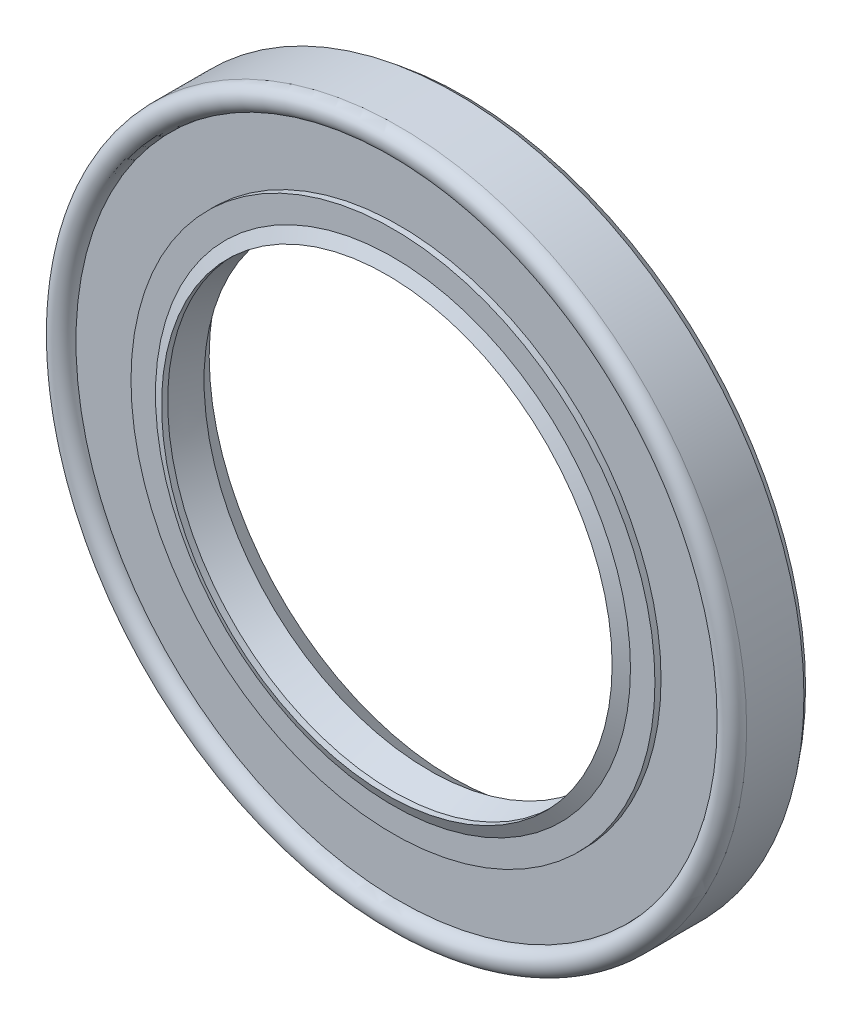
SolidWorks part; units mm, degrees
ref_plane "Front" through (0, 0, 0) normal (0, 0, 1) x (1, 0, 0)
ref_plane "Top" through (0, 0, 0) normal (0, 1, 0) x (1, 0, 0)
ref_plane "Right" through (0, 0, 0) normal (1, 0, 0) x (0, 0, -1)
sketch "Sketch1" plane through (0, 0, 0) normal (1, 0, 0) x (0, 0, -1)
  line L0 (-3.175, 17.5) -> (-2.7, 17.5)
  line L1 (-2.7, 17.5) -> (-2.225, 18.45)
  line L2 (-2.225, 18.45) -> (0.125, 17.5)
  line L3 (0.125, 17.5) -> (1.95, 18.925)
  line L4 (1.95, 18.925) -> (1.95, 19.4)
  line L5 (1.95, 19.4) -> (1.075, 19.4)
  line L6 (-0.825, 19.4) -> (-1.275, 19.4)
  line L7 (-1.275, 19.4) -> (-1.275, 26.05)
  line L8 (-1.275, 26.05) -> (1.625, 26.05)
  line L9 (1.625, 26.05) -> (1.625, 26.2875)
  line L10 (1.625, 26.2875) -> (2.225, 26.2875)
  line L11 (2.225, 26.2875) -> (2.225, 26.05)
  line L12 (2.225, 26.05) -> (2.825, 26.05)
  line L13 (2.825, 26.05) -> (2.825, 26.525)
  line L14 (2.825, 26.525) -> (2.225, 27)
  line L15 (2.225, 27) -> (-2.225, 27)
  line L16 (-2.225, 25.1) -> (-2.225, 20.35)
  line L17 (-2.225, 20.35) -> (-2.7, 20.35)
  line L18 (-2.7, 20.35) -> (-2.7, 18.45)
  line L19 (-2.7, 18.45) -> (-3.175, 17.5)
  line L20 (3.175, 0) -> (-3.175, 0) construction
  line L21 (-2.7, 17.5) -> (0.125, 17.5) construction
  line L22 (0, 27) -> (0, 26.05) construction
  line L23 (0, 26.05) -> (0, 25.1) construction
  line L24 (0, 25.1) -> (0, 24.15) construction
  line L25 (0, 24.15) -> (0, 23.2) construction
  line L26 (0, 23.2) -> (0, 22.25) construction
  line L27 (0, 22.25) -> (0, 21.3) construction
  line L28 (0, 21.3) -> (0, 20.35) construction
  line L29 (0, 20.35) -> (0, 19.4) construction
  line L30 (0, 19.4) -> (0, 18.45) construction
  line L31 (0, 18.45) -> (0, 17.5) construction
  line L32 (-3.175, 17.5) -> (-3.175, 26.05) construction
  line L33 (-3.175, 26.05) -> (-2.225, 26.05) construction
  line L34 (2.825, 26.05) -> (2.825, 17.5) construction
  line L35 (2.825, 17.5) -> (0.125, 17.5) construction
  line L36 (-3.175, 21.775) -> (-2.575, 21.775) construction
  line L37 (-2.575, 21.775) -> (-1.975, 21.775) construction
  line L38 (-1.975, 21.775) -> (-1.375, 21.775) construction
  line L39 (-1.375, 21.775) -> (-0.775, 21.775) construction
  line L40 (-0.775, 21.775) -> (-0.175, 21.775) construction
  line L41 (-0.175, 21.775) -> (0.425, 21.775) construction
  line L42 (0.425, 21.775) -> (1.025, 21.775) construction
  line L43 (1.025, 21.775) -> (1.625, 21.775) construction
  line L44 (1.625, 21.775) -> (2.225, 21.775) construction
  line L45 (2.225, 21.775) -> (2.825, 21.775) construction
  line L46 (0.125, 21.775) -> (0.125, 19.4) construction
  line L47 (0.125, 19.4) -> (0.125, 17.5) construction
  line L48 (2.225, 21.775) -> (2.225, 26.05) construction
  line L49 (1.625, 26.05) -> (1.625, 21.775) construction
  line L50 (2.225, 27) -> (2.225, 26.2875) construction
  line L51 (0, 25.1) -> (-2.225, 25.1) construction
  line L52 (-2.225, 20.35) -> (-2.225, 18.45) construction
  line L53 (1.95, 19.4) -> (2.825, 19.4) construction
  line L54 (-2.7, 26.05) -> (-2.7, 20.35) construction
  line L55 (-2.7, 19.4) -> (-1.275, 19.4) construction
  line L56 (2.225, 26.2875) -> (2.825, 26.2875) construction
  line L57 (-1.275, 22.725) -> (-2.225, 22.725) construction
  line L58 (1.95, 18.925) -> (0, 18.925) construction
  line L59 (-2.7, 18.45) -> (-2.225, 18.45) construction
  arc A0 (1.075, 19.4) -> (-0.825, 19.4) centre (0.125, 19.4) ccw construction
  arc A1 (-2.225, 27) -> (-2.225, 25.1) centre (-2.225, 26.05) ccw
  arc A2 (-0.825, 19.4) -> (1.075, 19.4) centre (0.125, 19.4) ccw
  dimension "SealWidth" = 6
  dimension "SealID" = 35
  dimension "SealOD" = 54
revolve "Revolve1" add sketch "Sketch1" angle 360 about L20
sketch "Sketch2" plane through (0, 0, 0) normal (1, 0, 0) x (0, 0, -1)
  line L0 (-3.175, 0) -> (3.175, 0) construction
  line L1 (-3.175, 26.05) -> (-3.175, -26.05) construction
  circle A0 centre (0.125, 19.4) radius 0.95
revolve "Revolve2" add sketch "Sketch2" angle 360 about L0
ref_plane "Contact Plane 1" [suppressed] through (0, 0, 2.95) normal (0, 0, 1) x (1, 0, 0)
